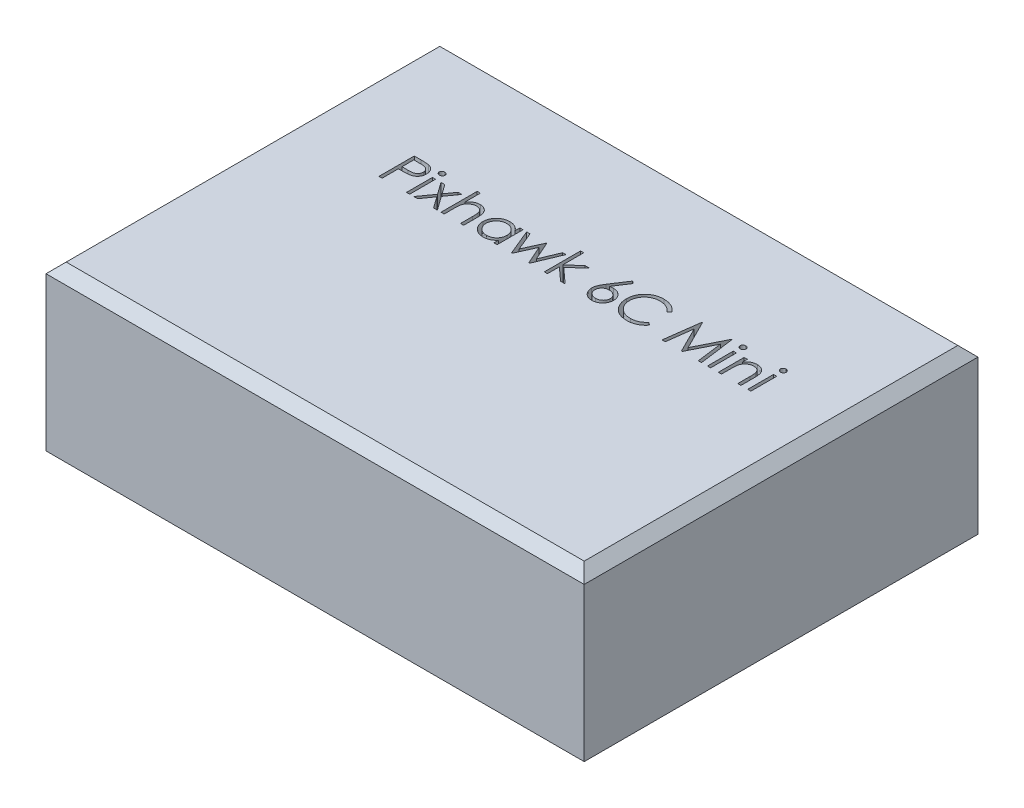
SolidWorks part; units mm, degrees
ref_plane "前视基准面" through (0, 0, 0) normal (0, 0, 1) x (1, 0, 0)
ref_plane "上视基准面" through (0, 0, 0) normal (0, 1, 0) x (1, 0, 0)
ref_plane "右视基准面" through (0, 0, 0) normal (1, 0, 0) x (0, 0, -1)
sketch "草图1" plane through (0, 0, 0) normal (0, 1, 0) x (1, 0, 0)
  line L1 (-26.65, 19.5) -> (26.65, 19.5)
  line L2 (-26.65, 19.5) -> (-26.65, -19.5)
  line L3 (-26.65, -19.5) -> (26.65, -19.5)
  line L4 (26.65, 19.5) -> (26.65, -19.5)
  line L5 (-26.65, 19.5) -> (26.65, -19.5) construction
  line L6 (-26.65, -19.5) -> (26.65, 19.5) construction
  point P0 (0, 0)
  dimension "D1" = 53.3
  dimension "D2" = 39
extrude "凸台-拉伸1" add sketch "草图1" along normal blind 16.2
chamfer "倒角1" distance 1 angle 45 1 edges at (0, 16.2, 19.5)
chamfer "倒角2" distance 1 angle 45 3 edges at (26.65, 16.2, -0.5) (0, 16.2, -19.5) (-26.65, 16.2, -0.5)
sketch "草图2" plane through (0, 16.2, 0) normal (0, 1, 0) x (1, 0, 0)
  text T0 "Pixhawk 6C Mini"
  point P1 (-10.6756, -0.3046)
extrude "切除-拉伸1" cut sketch "草图2" against normal blind 2
